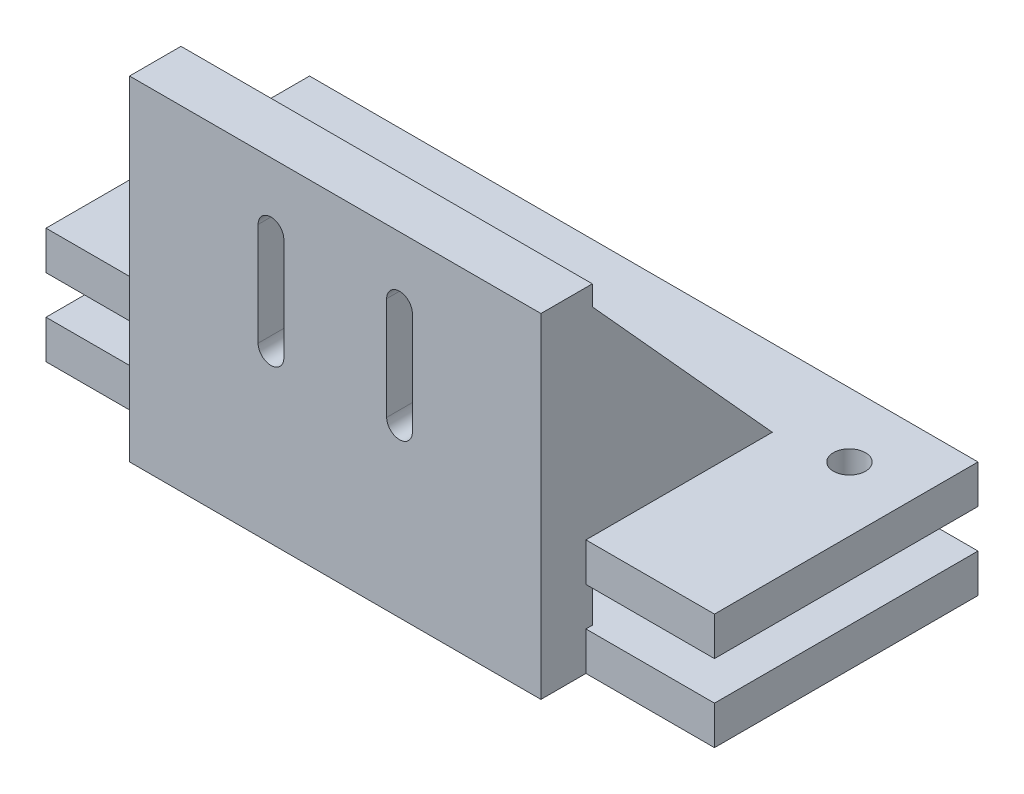
SolidWorks part; units mm, degrees
ref_plane "前视基准面" through (0, 0, 0) normal (0, 0, 1) x (1, 0, 0)
ref_plane "上视基准面" through (0, 0, 0) normal (0, 1, 0) x (1, 0, 0)
ref_plane "右视基准面" through (0, 0, 0) normal (1, 0, 0) x (0, 0, -1)
sketch "草图1" plane through (0, 0, 0) normal (0, 0, 1) x (1, 0, 0)
  line L1 (-32, -11.5) -> (32, -11.5)
  line L2 (-32, -11.5) -> (-32, 40.5)
  line L3 (-32, 40.5) -> (32, 40.5)
  line L4 (32, -11.5) -> (32, 40.5)
  line L5 (-32, -11.5) -> (32, 40.5) construction
  line L6 (-32, 40.5) -> (32, -11.5) construction
  point P0 (0, 14.5)
  dimension "D1" = 32
  dimension "D2" = 14.5
  dimension "D3" = 40.5
extrude "连接滑台背面_固定安装板" add sketch "草图1" along normal blind 8
sketch "草图2" plane through (0, 0, 0) normal (0, 0, 1) x (1, 0, 0)
  line L1 (-52, -11.5) -> (52, -11.5)
  line L2 (-52, -11.5) -> (-52, -5.5)
  line L3 (-52, -5.5) -> (52, -5.5)
  line L4 (52, -11.5) -> (52, -5.5)
  line L5 (-52, -11.5) -> (52, -5.5) construction
  line L6 (-52, -5.5) -> (52, -11.5) construction
  point P0 (0, -8.5)
  dimension "D1" = 52
  dimension "D2" = 5.5
  dimension "D3" = 8.5
extrude "下包边板_C槽净高6" add sketch "草图2" along normal blind 41 from offset 40
sketch "草图3" plane through (0, 0, 0) normal (0, 0, 1) x (1, 0, 0)
  line L1 (-52, 0.5) -> (52, 0.5)
  line L2 (-52, 0.5) -> (-52, 6.5)
  line L3 (-52, 6.5) -> (52, 6.5)
  line L4 (52, 0.5) -> (52, 6.5)
  line L5 (-52, 0.5) -> (52, 6.5) construction
  line L6 (-52, 6.5) -> (52, 0.5) construction
  point P0 (0, 3.5)
  dimension "D1" = 52
  dimension "D2" = 0.5
  dimension "D3" = 3.5
extrude "上包边板_C槽净高6" add sketch "草图3" along normal blind 41 from offset 40
sketch "草图4" plane through (0, 0, 0) normal (1, 0, 0) x (0, 0, -1)
  line L0 (28, 6.5) -> (-1, 6.5)
  line L1 (-1, 6.5) -> (-1, 38.5)
  line L2 (-1, 38.5) -> (28, 6.5)
  dimension "D1" = 28
  dimension "D2" = 1
  dimension "D3" = 6.5
  dimension "D4" = 38.5
extrude "侧边三角加强筋" add sketch "草图4" along normal blind 6 from offset 32
sketch "草图5" plane through (0, 0, 0) normal (1, 0, 0) x (0, 0, -1)
  line L0 (28, 6.5) -> (-1, 6.5)
  line L1 (-1, 6.5) -> (-1, 38.5)
  line L2 (-1, 38.5) -> (28, 6.5)
  dimension "D1" = 28
  dimension "D2" = 1
  dimension "D3" = 6.5
  dimension "D4" = 38.5
extrude "凸台-拉伸5" add sketch "草图5" along normal blind 6 from offset 26
sketch "草图6" plane through (0, 0, 0) normal (0, 0, 1) x (1, 0, 0)
  line L0 (-8, 14.5) -> (-8, 30.5)
  line L1 (-12, 30.5) -> (-12, 14.5)
  line L2 (12, 14.5) -> (12, 30.5)
  line L3 (8, 30.5) -> (8, 14.5)
  arc A0 (-8, 30.5) -> (-12, 30.5) centre (-10, 30.5) ccw
  arc A1 (-12, 14.5) -> (-8, 14.5) centre (-10, 14.5) ccw
  arc A2 (12, 30.5) -> (8, 30.5) centre (10, 30.5) ccw
  arc A3 (8, 14.5) -> (12, 14.5) centre (10, 14.5) ccw
  dimension "D1" = 2
  dimension "D2" = 10
  dimension "D3" = 10
  dimension "D4" = 14.5
  dimension "D5" = 30.5
extrude "上下可调槽_中心行程正负8" cut sketch "草图6" along normal blind 8
sketch "草图7" plane through (0, 0, 0) normal (0, 1, 0) x (1, 0, 0)
  circle A0 centre (-42, 30) radius 2.5
  circle A1 centre (42, 30) radius 2.5
  dimension "D1" = 5
  dimension "D2" = 42
  dimension "D3" = 42
  dimension "D4" = 30
extrude "两翼共用车板孔_不直接攻塑料牙" cut sketch "草图7" along normal blind 18 from offset 11.5
